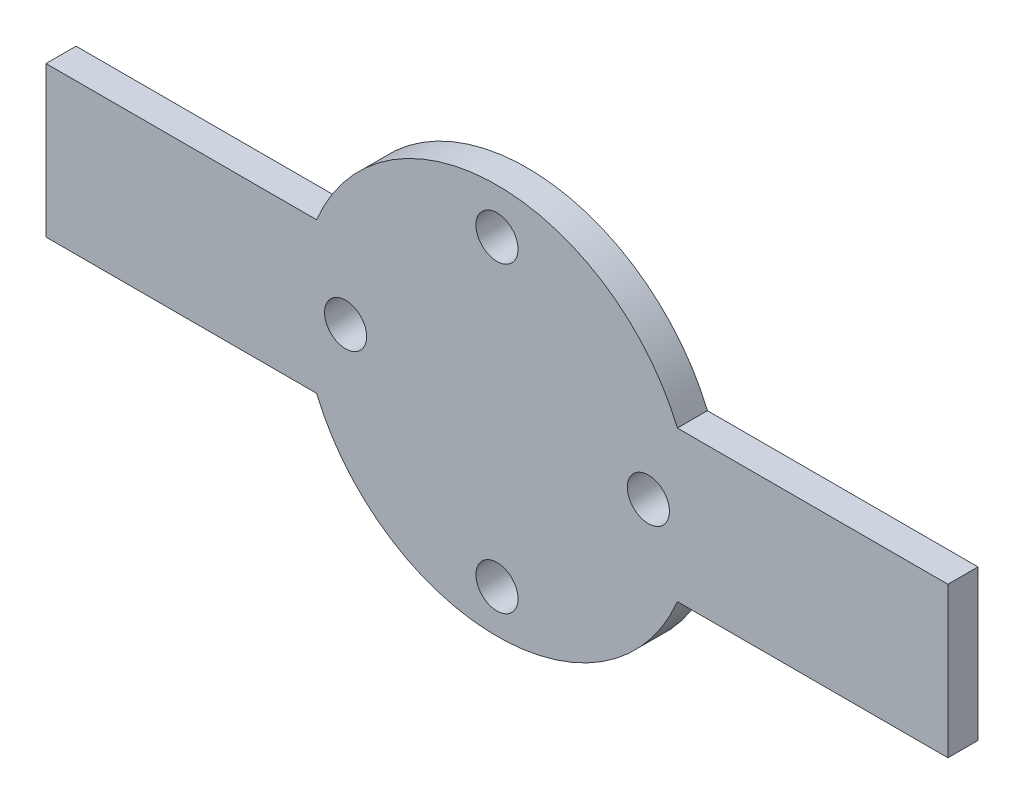
SolidWorks part; units mm, degrees
ref_plane "Ebene vorne" through (0, 0, 0) normal (0, 0, 1) x (1, 0, 0)
ref_plane "Ebene oben" through (0, 0, 0) normal (0, 1, 0) x (1, 0, 0)
ref_plane "Ebene rechts" through (0, 0, 0) normal (1, 0, 0) x (0, 0, -1)
sketch "Skizze1" plane through (0, 0, 0) normal (0, 0, 1) x (1, 0, 0)
  circle A0 centre (0, 0) radius 32.5
  dimension "D1" = 65
extrude "Aufsatz-Linear austragen1" add sketch "Skizze1" along normal blind 5
sketch "Skizze2" plane through (0, 0, 0) normal (0, 0, -1) x (-1, 0, 0)
  circle A0 centre (0, 25) radius 3.5
  dimension "D1" = 7
  dimension "D2" = 25
extrude "Schnitt-Linear austragen1" cut sketch "Skizze2" against normal blind 10
sketch "Skizze3" plane through (0, 0, 0) normal (0, 0, -1) x (-1, 0, 0)
  line L1 (-75, 12.5) -> (75, 12.5)
  line L2 (-75, 12.5) -> (-75, -12.5)
  line L3 (-75, -12.5) -> (75, -12.5)
  line L4 (75, 12.5) -> (75, -12.5)
  line L5 (-75, 12.5) -> (75, -12.5) construction
  line L6 (-75, -12.5) -> (75, 12.5) construction
  point P0 (0, 0)
  dimension "D1" = 25
  dimension "D2" = 150
extrude "Aufsatz-Linear austragen2" add sketch "Skizze3" against normal blind 5
pattern_circular "Kreismuster1" count 4 over 360 about axis through (0, -0.1767, 0) along (0, 0, 1) of "Schnitt-Linear austragen1"
